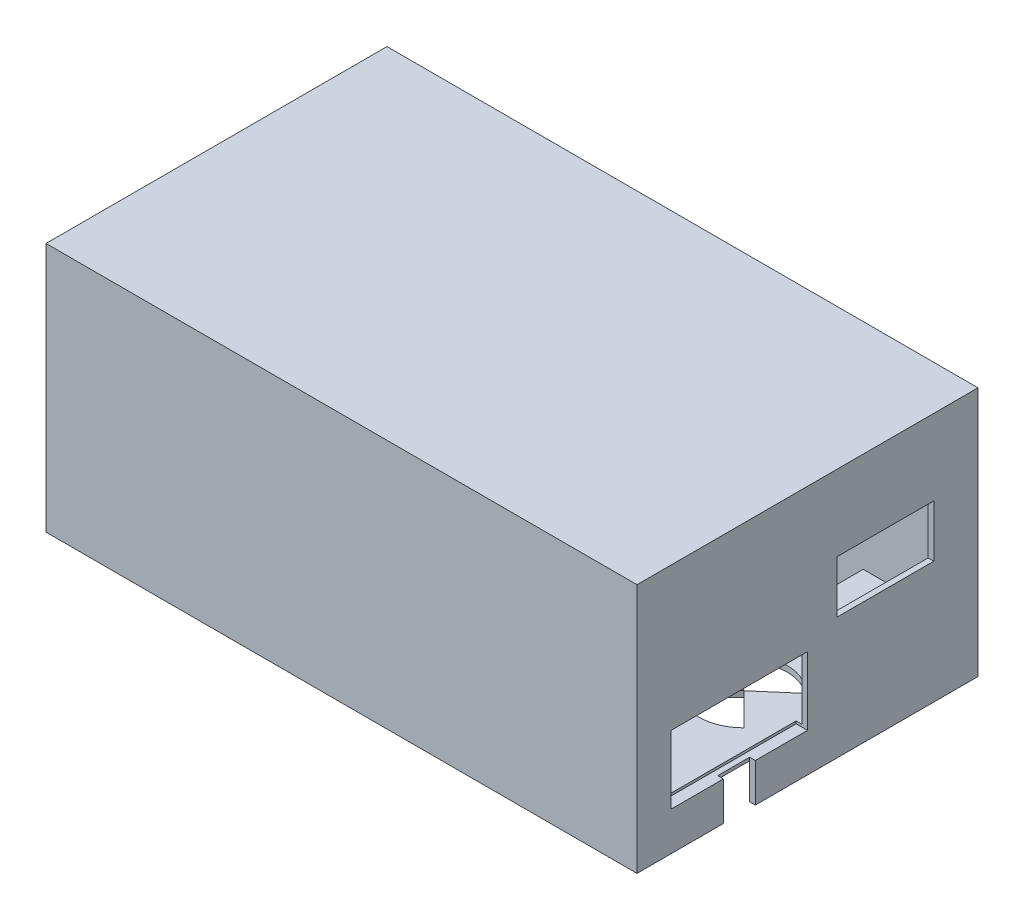
SolidWorks part; units mm, degrees
ref_plane "Front Plane" through (0, 0, 0) normal (0, 0, 1) x (1, 0, 0)
ref_plane "Top Plane" through (0, 0, 0) normal (0, 1, 0) x (1, 0, 0)
ref_plane "Right Plane" through (0, 0, 0) normal (1, 0, 0) x (0, 0, -1)
sketch "Sketch1" plane through (0, 0, 0) normal (0, 1, 0) x (1, 0, 0)
  line L0 (2.5, 150) -> (2.5, 147.5) construction
  line L1 (0, 0) -> (260, 0)
  line L2 (0, 0) -> (0, 150)
  line L3 (0, 150) -> (260, 150)
  line L4 (260, 0) -> (260, 150)
  line L5 (2.5, 147.5) -> (0, 147.5) construction
  line L6 (0, 2.5) -> (2.5, 2.5) construction
  line L7 (2.5, 2.5) -> (2.5, 0) construction
  line L8 (257.5, 150) -> (257.5, 147.5) construction
  line L9 (257.5, 147.5) -> (260, 147.5) construction
  line L10 (260, 2.5) -> (257.5, 2.5) construction
  line L11 (257.5, 2.5) -> (257.5, 0) construction
  line L12 (2.5, 147.5) -> (2.5, 2.5)
  line L13 (2.5, 2.5) -> (257.5, 2.5)
  line L14 (257.5, 2.5) -> (257.5, 147.5)
  line L15 (257.5, 147.5) -> (2.5, 147.5)
  dimension "D1" = 260
  dimension "D2" = 150
  dimension "D3" = 2.5
  dimension "D4" = 2.5
  dimension "D5" = 2.5
  dimension "D6" = 2.5
  dimension "D7" = 2.5
  dimension "D8" = 2.5
  dimension "D9" = 2.5
  dimension "D10" = 2.5
extrude "Boss-Extrude1" add sketch "Sketch1" against normal blind 110
sketch "Sketch2" plane through (0, 0, 0) normal (0, 1, 0) x (1, 0, 0)
  line L0 (2.5, 147.5) -> (257.5, 147.5)
  line L1 (257.5, 147.5) -> (257.5, 2.5)
  line L2 (257.5, 2.5) -> (2.5, 2.5)
  line L3 (2.5, 2.5) -> (2.5, 147.5)
extrude "Boss-Extrude2" add sketch "Sketch2" against normal blind 2.5
sketch "Sketch3" plane through (0, -110, 0) normal (0, -1, 0) x (1, 0, 0)
  line L0 (0, -150) -> (212, -150) construction
  line L1 (260, -150) -> (0, -150) construction
  line L2 (212, -150) -> (212, 0) construction
  line L3 (0, 0) -> (260, 0) construction
  line L5 (212, -54.6346) -> (257.5, -54.6346) construction
  line L6 (257.5, -2.5) -> (257.5, -147.5) construction
  line L8 (217.8579, -60.8579) -> (232, -75)
  line L9 (232, -75) -> (246.1421, -60.8579)
  line L10 (232, -75) -> (217.8579, -60.8579) construction
  line L12 (232, -75) -> (246.1421, -60.8579) construction
  arc A2 (246.1421, -60.8579) -> (217.8579, -60.8579) centre (232, -75) ccw
  dimension "D1" = 212
sketch "Sketch4" plane through (257.5, 0, 0) normal (-1, 0, 0) x (0, 0, 1)
  line L2 (-2.5, -94.4) -> (-2.5, -91.9)
  line L3 (-2.5, -110) -> (-2.5, -2.5) construction
  line L4 (-2.5, -91.9) -> (-147.5, -91.9)
  line L5 (-147.5, -110) -> (-147.5, -2.5) construction
  line L6 (-147.5, -91.9) -> (-147.5, -94.4)
  line L7 (-147.5, -94.4) -> (-2.5, -94.4)
  line L10 (-150, -110) -> (0, -110) construction
  dimension "D1" = 18.1
  dimension "D2" = 2.5
  dimension "D3" = 2.5
  dimension "D4" = 18.1
extrude "Boss-Extrude3" add sketch "Sketch4" along normal blind 45.5
sketch "Sketch5" plane through (0, -94.4, 0) normal (0, -1, 0) x (1, 0, 0)
  line L0 (217.8579, -60.8579) -> (232, -75)
  line L1 (232, -75) -> (246.1421, -60.8579)
  line L2 (246.1421, -60.8579) -> (257.5, -60.8579)
  line L3 (257.5, -147.5) -> (257.5, -2.5) construction
  arc A0 (246.1411, -60.8589) -> (217.8589, -60.8589) centre (232, -75) ccw
  dimension "D1" = 19.9986
extrude "Cut-Extrude-Thin4" cut sketch "Sketch5" against normal blind 5 thin
sketch "Sketch6" plane through (260, 0, 0) normal (1, 0, 0) x (0, 0, -1)
  line L0 (0, -110) -> (0, -93) construction
  line L1 (0, -110) -> (0, 0) construction
  line L2 (0, -93) -> (150, -93) construction
  line L3 (150, -110) -> (150, 0) construction
  line L4 (75, -110) -> (75, -93)
  line L5 (0, -110) -> (150, -110) construction
  line L6 (75, -93) -> (15, -93)
  line L7 (15, -93) -> (15, -63)
  line L8 (15, -63) -> (75, -63)
  line L9 (75, -63) -> (75, -93)
  dimension "D1" = 17
  dimension "D2" = 60
  dimension "D3" = 30
extrude "Cut-Extrude1" cut sketch "Sketch6" against normal blind 5 contours L9 L8 L7 L6
sketch "Sketch8" plane through (0, 0, -75) normal (0, 0, 1) x (1, 0, 0)
  line L0 (260, -63) -> (257.5, -64.6478)
  line L1 (257.5, -63) -> (257.5, -91.9) construction
  line L2 (257.5, -63) -> (260, -63) construction
  line L3 (257.5, -64.6478) -> (257.5, -63)
  line L4 (257.5, -63) -> (260, -63)
  dimension "D1" = 33.39
extrude "Boss-Extrude4" add sketch "Sketch8" along normal up to next
sketch "Sketch9" plane through (0, -94.4, 0) normal (0, -1, 0) x (1, 0, 0)
  line L0 (232, -75) -> (246.4793, -87.467)
  line L1 (232, -75) -> (217.5207, -87.467)
  arc A0 (217.5207, -87.467) -> (246.4793, -87.467) centre (232, -75) ccw
extrude "Cut-Extrude2" cut sketch "Sketch9" against normal blind 3
sketch "Sketch10" plane through (260, 0, 0) normal (1, 0, 0) x (0, 0, -1)
  line L0 (150, -33.34) -> (130.57, -33.34) construction
  line L1 (150, -110) -> (150, 0) construction
  line L2 (130.57, -33.34) -> (130.57, 0) construction
  line L3 (0, 0) -> (150, 0) construction
  line L5 (130.57, -33.34) -> (88, -33.34)
  line L6 (130.57, -33.34) -> (130.57, -56.34)
  line L7 (130.57, -56.34) -> (88, -56.34)
  line L8 (88, -33.34) -> (88, -56.34)
  dimension "D1" = 19.43
  dimension "D2" = 33.34
  dimension "D3" = 42.57
  dimension "D4" = 23
extrude "Cut-Extrude3" cut sketch "Sketch10" against normal blind 2.5
sketch "Sketch11" plane through (260, 0, 0) normal (1, 0, 0) x (0, 0, -1)
  line L0 (45, -93) -> (37.965, -93)
  line L1 (75, -93) -> (15, -93) construction
  line L2 (45, -93) -> (52.035, -93)
  line L3 (37.965, -93) -> (37.965, -110)
  line L4 (0, -110) -> (150, -110) construction
  line L5 (37.965, -110) -> (52.035, -110)
  line L6 (52.035, -110) -> (52.035, -93)
  dimension "D1" = 7.035
  dimension "D2" = 7.035
extrude "Cut-Extrude4" cut sketch "Sketch11" against normal blind 2.5
